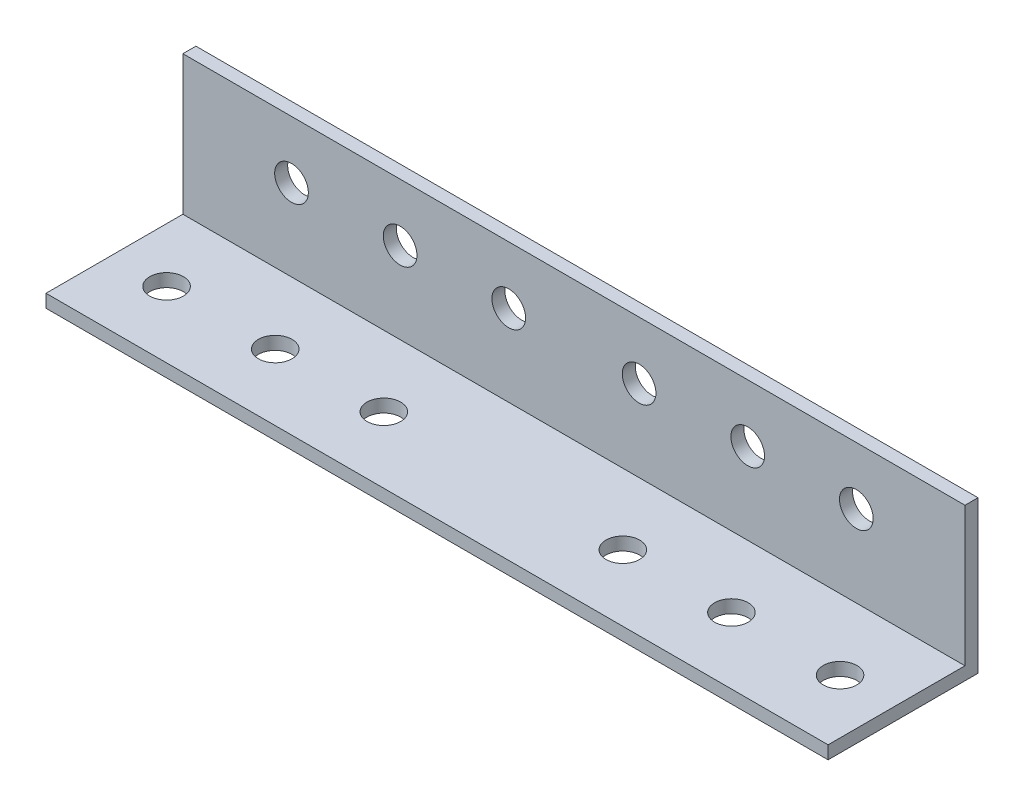
SolidWorks part; units mm, degrees
ref_plane "Front Plane" through (0, 0, 0) normal (0, 0, 1) x (1, 0, 0)
ref_plane "Top Plane" through (0, 0, 0) normal (0, 1, 0) x (1, 0, 0)
ref_plane "Right Plane" through (0, 0, 0) normal (1, 0, 0) x (0, 0, -1)
sketch "Sketch1" plane through (0, 0, 0) normal (0, 0, 1) x (1, 0, 0)
  line L1 (0, 0) -> (720, 0)
  line L2 (0, 0) -> (0, 140)
  line L3 (0, 140) -> (720, 140)
  line L4 (720, 0) -> (720, 140)
  circle A0 centre (100, 87) radius 15.5
  circle A1 centre (200, 87) radius 15.5
  circle A2 centre (300, 87) radius 15.5
  circle A3 centre (520, 87) radius 15.5
  circle A4 centre (620, 87) radius 15.5
  circle A5 centre (420, 87) radius 15.5
  dimension "D3" = 31
  dimension "D6" = 31
  dimension "D7" = 31
  dimension "D12" = 31
  dimension "D13" = 31
  dimension "D14" = 31
  dimension "D1" = 140
  dimension "D2" = 720
  dimension "D4" = 87
  dimension "D5" = 100
  dimension "D8" = 100
  dimension "D9" = 100
  dimension "D10" = 87
  dimension "D11" = 87
  dimension "D15" = 100
  dimension "D16" = 100
  dimension "D17" = 120
  dimension "D18" = 87
  dimension "D19" = 87
  dimension "D20" = 87
extrude "Extrude1" add sketch "Sketch1" along normal blind 12
sketch "Sketch2" plane through (0, 0, 12) normal (0, 0, 1) x (1, 0, 0)
  line L0 (720, 0) -> (720, 140) construction
  line L1 (0, 0) -> (720, 0)
  line L2 (0, 0) -> (0, 12)
  line L3 (0, 12) -> (720, 12)
  line L4 (720, 0) -> (720, 12)
  dimension "D1" = 12
extrude "Extrude2" add sketch "Sketch2" along normal blind 126
sketch "Sketch3" plane through (0, 12, 0) normal (0, 1, 0) x (1, 0, 0)
  line L0 (0, -138) -> (0, -12) construction
  line L1 (720, 0) -> (0, 0) construction
  circle A0 centre (50, -77) radius 15.5
  circle A1 centre (150, -77) radius 15.5
  circle A2 centre (250, -77) radius 15.5
  circle A3 centre (670, -77) radius 15.5
  circle A4 centre (470, -77) radius 15.5
  circle A5 centre (570, -77) radius 15.5
  dimension "D1" = 31
  dimension "D4" = 31
  dimension "D5" = 31
  dimension "D10" = 31
  dimension "D11" = 31
  dimension "D12" = 31
  dimension "D2" = 50
  dimension "D3" = 77
  dimension "D6" = 100
  dimension "D7" = 100
  dimension "D8" = 77
  dimension "D9" = 77
  dimension "D13" = 100
  dimension "D14" = 100
  dimension "D15" = 220
  dimension "D16" = 77
  dimension "D17" = 77
  dimension "D18" = 77
extrude "Extrude3" cut sketch "Sketch3" against normal blind 168
